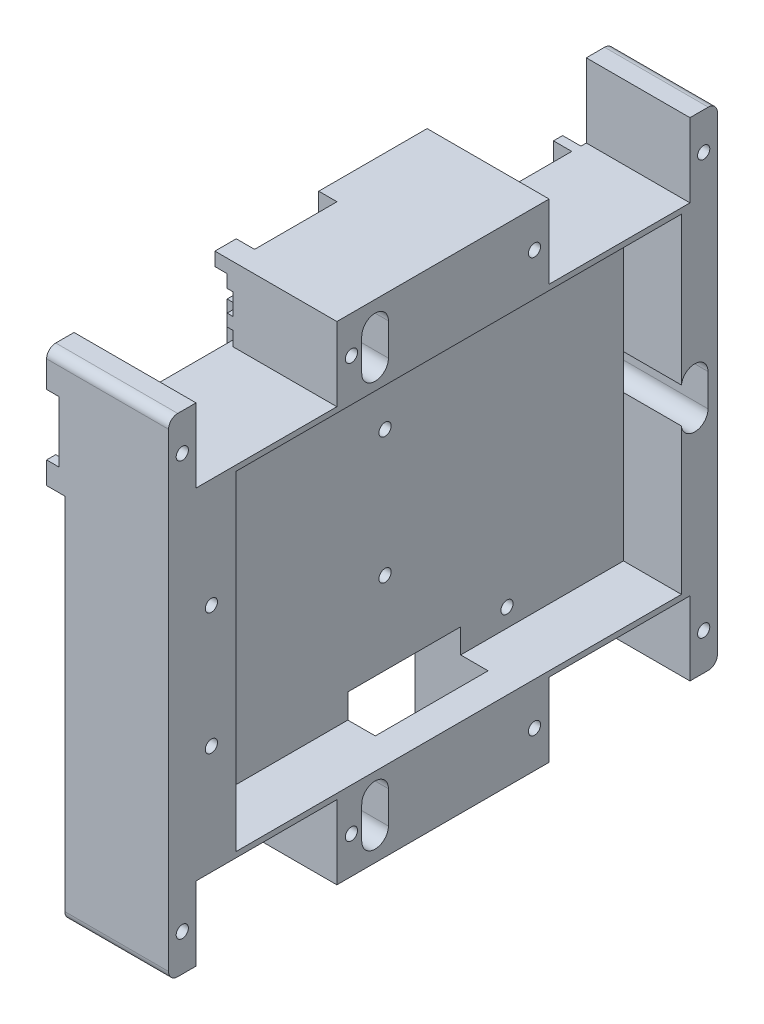
SolidWorks part; units mm, degrees
ref_plane "Спереди" through (0, 0, 0) normal (0, 0, 1) x (1, 0, 0)
ref_plane "Сверху" through (0, 0, 0) normal (0, 1, 0) x (1, 0, 0)
ref_plane "Справа" through (0, 0, 0) normal (1, 0, 0) x (0, 0, -1)
other "Configuration Table"
sketch "Эскиз1" plane through (0, 0, 0) normal (1, 0, 0) x (0, 0, -1)
  line L0 (0, 0) -> (-45, 0) construction
  line L1 (0, 0) -> (45, 0) construction
  line L2 (0, 0) -> (0, -40) construction
  line L3 (0, 0) -> (0, 40) construction
  line L4 (0, 40) -> (-17.4, 40)
  line L5 (-45, 40) -> (-45, -40)
  line L6 (-45, -40) -> (-40.5, -40)
  line L7 (45, -40) -> (45, 40)
  line L8 (45, 40) -> (40.5, 40)
  line L9 (0, 0) -> (0, -9.5) construction
  line L10 (40.5, 40) -> (40.5, 27.9)
  line L11 (-40.5, -40) -> (-40.5, -27.9)
  line L12 (17.4, -27.9) -> (17.4, -40)
  line L13 (-40.5, -27.9) -> (-17.4, -27.9)
  line L14 (-17.4, -27.9) -> (-17.4, -40)
  line L15 (-17.4, -40) -> (17.4, -40)
  line L16 (40.5, -27.9) -> (17.4, -27.9)
  line L17 (40.5, -40) -> (40.5, -27.9)
  line L18 (40.5, 27.9) -> (17.4, 27.9)
  line L19 (17.4, 27.9) -> (17.4, 40)
  line L20 (-17.4, 27.9) -> (-17.4, 40)
  line L21 (-40.5, 27.9) -> (-17.4, 27.9)
  line L22 (-40.5, 40) -> (-40.5, 27.9)
  line L23 (-40.5, 40) -> (-45, 40)
  line L24 (17.4, 40) -> (0, 40)
  line L25 (40.5, -40) -> (45, -40)
  line L26 (0, 0) -> (0, 11.2403) construction
  line L27 (3.8246, -24) -> (3.8246, 24) construction
  line L28 (-83.3461, -24) -> (100.3156, -24) construction
  line L29 (-83.3461, 24) -> (100.3156, 24) construction
  line L30 (45, 18.124) -> (20, 18.124) construction
  line L31 (-17.4, -36.7227) -> (-15.0096, -36.7227) construction
  line L32 (20, 15.0688) -> (-30.9, 15.0688) construction
  line L33 (20, 43.3893) -> (20, -36.7227) construction
  line L34 (-30.9, 15.0688) -> (-30.9, 50.8075) construction
  line L35 (-30.9, 50.8075) -> (-30.9, -42.0727) construction
  line L36 (-37.9745, 0) -> (-37.9745, -10) construction
  line L37 (-28.95, -27.9) -> (-28.95, -44.7692) construction
  line L38 (-50.7237, -33.95) -> (-10.6217, -33.95) construction
  circle A2 centre (-42.75, -33.95) radius 1
  circle A3 centre (-15.0096, -33.95) radius 1
  circle A4 centre (15.0096, -33.95) radius 1
  circle A5 centre (42.75, -33.95) radius 1
  circle A6 centre (42.75, 33.95) radius 1
  circle A7 centre (15.0096, 33.95) radius 1
  circle A8 centre (-15.0096, 33.95) radius 1
  circle A9 centre (-42.75, 33.95) radius 1
  circle A10 centre (20, 24) radius 1
  circle A11 centre (20, -24) radius 1
  circle A12 centre (-30.9, -9) radius 1
  circle A13 centre (-30.9, 19) radius 1
  circle A14 centre (-37.9745, -10) radius 1
  circle A15 centre (-37.9745, 10) radius 1
  circle A16 centre (0, 11.2403) radius 1
  circle A17 centre (0, -9.5) radius 1
  point P15 (3.8246, 0)
  point P80 (0, 0)
extrude "Бобышка-Вытянуть1" add sketch "Эскиз1" along normal blind 17
fillet "Скругление1" radius 1.5 4 edges at (8.5, -40, -45) (8.5, -40, 45) (8.5, 40, -45) (8.5, 40, 45)
sketch "Эскиз2" plane through (17, 0, 0) normal (1, 0, 0) x (0, 0, -1)
  line L0 (0, 0) -> (-78.3031, 0) construction
  line L1 (-20.352, -27) -> (-20.352, 27) construction
  line L2 (-30.9, 19) -> (-33.9, 19) construction
  line L3 (-33.9, 27) -> (-33.9, -27)
  line L4 (-33.9, -27) -> (39.1, -27)
  line L5 (39.1, -27) -> (39.1, 27)
  line L6 (39.1, 27) -> (-33.9, 27)
  point P6 (-20.352, 0)
extrude "Вырез-Вытянуть1" cut sketch "Эскиз2" against normal blind 9.5
ref_plane "Плоскость1" through (0, -38.5, 0) normal (0, -1, 0) x (-1, 0, 0)
sketch "Эскиз4" plane through (17, 0, 0) normal (1, 0, 0) x (0, 0, -1)
  line L0 (-17.4, 33.95) -> (17.4, 33.95) construction
  line L1 (-17.4, 40) -> (-17.4, 27.9) construction
  line L2 (17.4, 27.9) -> (17.4, 40) construction
  line L3 (0.69, -30.3907) -> (-7.7794, -30.3907) construction
  line L4 (0.69, -30.3907) -> (-2.4794, -30.3907) construction
  line L6 (-4.4188, -32.4907) -> (-4.4188, -38.5) construction
  line L9 (-4.4188, -30.5) -> (-4.4188, -28.4) construction
  line L10 (-4.4188, -30.5) -> (-4.4188, -32.4907) construction
  line L13 (-1.2514, 0) -> (29.4657, 0) construction
  line L16 (-9.35, -38.5) -> (9.35, -38.5) construction
  line L28 (29.4657, 0) -> (52.3622, 0) construction
  line L29 (-11.1338, -30.5707) -> (-11.1338, -37.2973) construction
  line L32 (-8.9466, -30.5707) -> (-8.9466, -35.8707)
  line L33 (-13.3206, -30.6072) -> (-13.3209, -35.8707)
  line L34 (43.4593, 2.4723) -> (43.4593, -2.8277)
  line L35 (39.0852, 2.4359) -> (39.0849, -2.8277)
  line L36 (-13.3206, 30.6072) -> (-13.3206, 35.8707)
  line L38 (-8.9469, 35.8707) -> (-8.9466, 30.5707)
  arc A7 (-8.9466, 30.5707) -> (-13.3206, 30.6072) centre (-11.1338, 30.5707) cw
  arc A20 (-8.9466, -30.5707) -> (-13.3206, -30.6072) centre (-11.1338, -30.5707) ccw
  arc A21 (-8.9466, -35.8707) -> (-13.3209, -35.8707) centre (-11.1338, -35.8707) cw
  arc A22 (43.4593, 2.4723) -> (39.0852, 2.4359) centre (41.2721, 2.4723) ccw
  arc A23 (43.4593, -2.8277) -> (39.0849, -2.8277) centre (41.2721, -2.8277) cw
  arc A24 (-13.3206, 35.8707) -> (-8.9469, 35.8707) centre (-11.1338, 35.8707) cw
extrude "Вырез-Вытянуть2" cut sketch "Эскиз4" against normal through all
sketch "Эскиз5" plane through (0, 0, 0) normal (-1, 0, 0) x (0, 0, 1)
  line L0 (15.4, 37.8) -> (17.4, 37.8)
  line L5 (38, 20.5) -> (-38, -20.5) construction
  line L6 (38, -20.5) -> (-38, 20.5) construction
  line L8 (45, 22.325) -> (43.5, 22.325) construction
  line L22 (45, 34.15) -> (43.7298, 34.15)
  line L23 (15.4, 20.5) -> (15.4, 32.2)
  line L26 (17.4, 40) -> (17.4, 27.9) construction
  line L27 (40.5, 37.8) -> (40.5, 39.3)
  line L29 (13.9, 39.3) -> (13.9, 35.7)
  line L30 (13.9, 20.5) -> (15.4, 20.5)
  line L32 (40.5, 27.9) -> (40.5, 40) construction
  line L35 (45, 38.5) -> (45, 34.15)
  line L43 (15.4, 35.7) -> (15.4, 37.8)
  line L45 (17.4, 40) -> (17.4, 37.8)
  line L46 (13.9, 39.3) -> (13.9, 40)
  line L47 (-17.4, 40) -> (17.4, 40) construction
  line L48 (13.9, 40) -> (17.4, 40)
  line L51 (45, 38.5) -> (45, -38.5) construction
  line L52 (45, 24.15) -> (43.5, 24.15)
  line L54 (43.5, 24.15) -> (43.5, 20.5)
  line L55 (45, 24.15) -> (45, 20.5)
  line L56 (45, 20.5) -> (43.5, 20.5)
  line L57 (40.5, 39.3) -> (40.5, 40)
  line L58 (40.5, 40) -> (43.5, 40)
  line L59 (43.5, 34.6114) -> (43.5, 37.8)
  line L60 (43.5, 37.8) -> (40.5, 37.8)
  line L61 (17.4, 33.95) -> (5.2507, 33.95) construction
  line L62 (17.4, 40) -> (17.4, 27.9) construction
  line L63 (15.0096, 33.95) -> (15.0096, 35.7) construction
  line L64 (15.4, 35.7) -> (13.9, 35.7)
  line L65 (15.4, 32.2) -> (13.9, 32.2)
  line L66 (13.9, 32.2) -> (13.9, 20.5)
  arc A0 (43.5, 40) -> (45, 38.5) centre (43.5, 38.5) cw
  arc A2 (43.7298, 34.15) -> (43.5, 34.6114) centre (42.75, 33.95) ccw
  point P0 (0, 0)
  point P21 (45, 30.8066)
  point P22 (45, 29.15)
extrude "Бобышка-Вытянуть4" add sketch "Эскиз5" along normal blind 3
sketch "Эскиз6" plane through (0, 0, 0) normal (-1, 0, 0) x (0, 0, 1)
  line L0 (15.4, 37.8) -> (17.4, 37.8)
  line L1 (15.4, 37.8) -> (15.4, 35.7)
  line L2 (15.4, 35.7) -> (17.4, 35.7)
  line L3 (17.4, 37.8) -> (17.4, 27.9) construction
  line L4 (17.4, 35.7) -> (17.4, 37.8)
  line L5 (15.4, 20.5) -> (43.5, 20.5)
  line L6 (43.5, 20.5) -> (43.5, 22.5232)
  line L7 (43.5, 24.15) -> (43.5, 20.5) construction
  line L8 (43.5, 22.5232) -> (15.4, 22.5232)
  line L9 (15.4, 20.5) -> (15.4, 32.2) construction
  line L10 (15.4, 22.5232) -> (15.4, 20.5)
  line L12 (45, 34.15) -> (45, 24.15) construction
  line L13 (45, 27.9) -> (45, 24.15)
  line L14 (45, 24.15) -> (43.5, 24.15)
  line L16 (15.4, 25.7755) -> (15.4, 27.9)
  line L17 (15.4, 27.9) -> (40.5, 27.9)
  line L18 (43.5, 24.15) -> (43.5, 25.7755)
  line L19 (41.7702, 25.7755) -> (15.4, 25.7755)
  line L20 (45, 27.9) -> (45, 34.15)
  line L21 (45, 34.15) -> (43.7298, 34.15)
  line L22 (40.5, 27.9) -> (40.5, 37.8) construction
  line L23 (40.5, 34.15) -> (40.5, 27.9)
  line L24 (41.7702, 34.15) -> (40.5, 34.15)
  line L25 (43.5, 25.7755) -> (43.5, 33.2886)
  line L26 (41.7702, 33.75) -> (41.7702, 25.7755)
  line L27 (15.4, 32.2) -> (17.4, 32.2)
  line L28 (17.4, 32.2) -> (17.4, 30.2272)
  line L29 (17.4, 30.2272) -> (15.4, 30.2272)
  line L30 (15.4, 30.2272) -> (15.4, 32.2)
  arc A0 (41.7702, 34.15) -> (41.7702, 33.75) centre (42.75, 33.95) ccw
  arc A1 (43.5, 33.2886) -> (43.7298, 34.15) centre (42.75, 33.95) ccw
extrude "Бобышка-Вытянуть5" add sketch "Эскиз6" along normal blind 1
sketch "Эскиз8" plane through (0, 0, 0) normal (-1, 0, 0) x (0, 0, 1)
sketch "Эскиз9" plane through (0, 0, 0) normal (-1, 0, 0) x (0, 0, 1)
  line L0 (13.9, 20.5) -> (-45, 20.5) construction
  line L1 (-45, -38.5) -> (-45, 38.5) construction
  line L2 (0.3794, 37.5) -> (0.3794, 20.5)
  line L3 (0.3794, 20.5) -> (-1.1206, 20.5)
  line L4 (-17.4, 27.9) -> (-17.4, 40) construction
  line L5 (-17.4, 37.5) -> (-17.4, 40)
  line L6 (-1.1206, 37.5) -> (-1.1206, 20.5)
  line L7 (0.3794, 37.5) -> (0.3794, 40)
  line L8 (-17.4, 40) -> (13.9, 40) construction
  line L9 (0.3794, 40) -> (-17.4, 40)
  line L10 (-17.4, 37.5) -> (-1.1206, 37.5)
  line L12 (-38.1206, 27.9) -> (-38.1206, 20.5)
  line L13 (-38.1206, 20.5) -> (-39.6206, 20.5)
  line L14 (-39.6206, 20.5) -> (-39.6206, 27.9)
  line L15 (-40.5, 27.9) -> (-17.4, 27.9) construction
  line L16 (-39.6206, 27.9) -> (-38.1206, 27.9)
extrude "Бобышка-Вытянуть6" add sketch "Эскиз9" along normal blind 3
sketch "Эскиз10" plane through (0, 0, 0) normal (-1, 0, 0) x (0, 0, 1)
  line L0 (-17.4, -35.021) -> (-12.4, -35.021) construction
  line L1 (-17.4, -40) -> (-17.4, -27.9) construction
  line L2 (-12.4, -35.021) -> (6.1, -35.021) construction
  line L3 (-12.4, -40) -> (-12.4, -23)
  line L4 (17.4, -40) -> (-17.4, -40) construction
  line L5 (-12.4, -23) -> (6.1, -23)
  line L6 (6.1, -23) -> (6.1, -40)
  line L7 (6.1, -40) -> (-12.4, -40)
extrude "Вырез-Вытянуть3" cut sketch "Эскиз10" against normal blind 12
